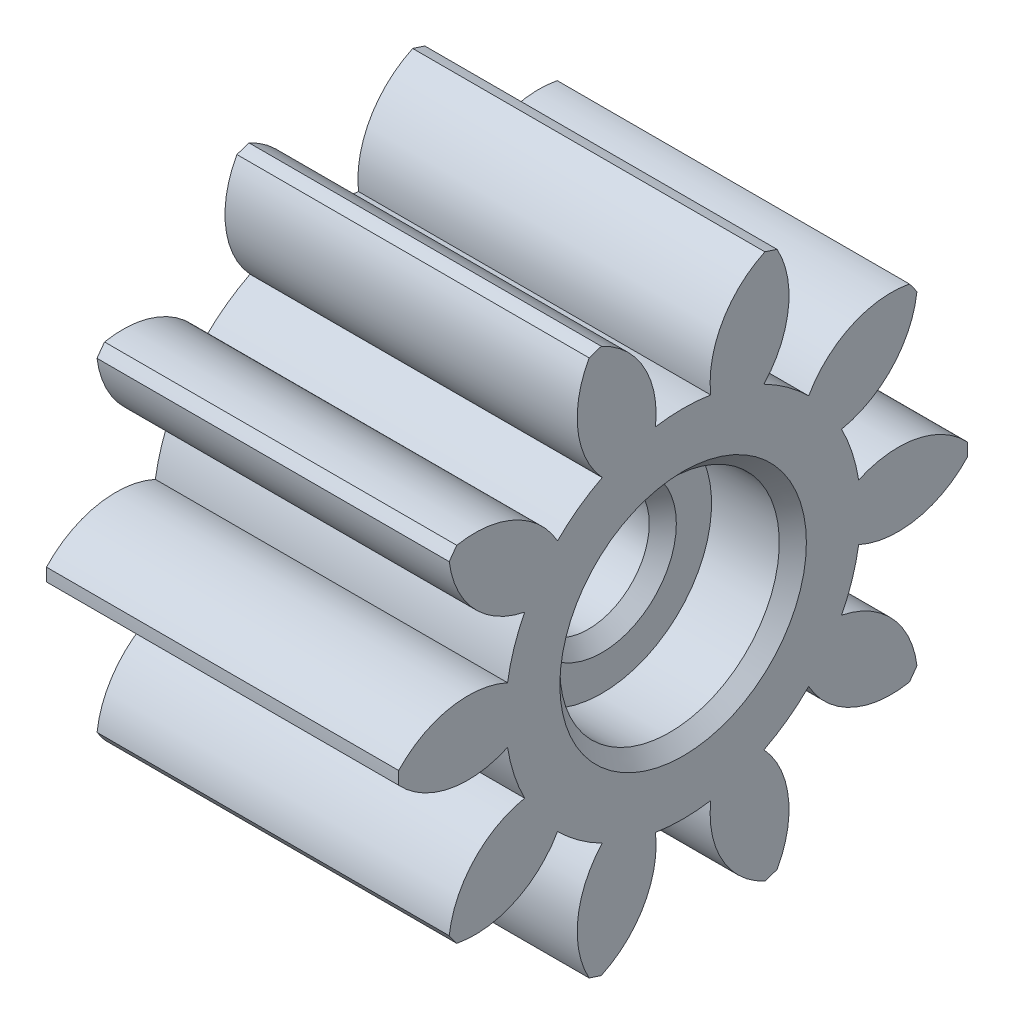
SolidWorks part; units mm, degrees
ref_plane "Plane1" through (0, 0, 0) normal (0, 0, 1) x (1, 0, 0)
ref_plane "Plane2" through (0, 0, 0) normal (0, 1, 0) x (1, 0, 0)
ref_plane "Plane3" through (0, 0, 0) normal (1, 0, 0) x (0, 0, -1)
sketch "HoldingSke" plane through (0, 0, 0) normal (0, 1, 0) x (1, 0, 0)
  line L0 (0, 0) -> (0.5627, -0.0992)
  line L1 (-15, 0) -> (100, 0) construction
  line L2 (0, 0) -> (-2.1039, 2.3779)
  line L3 (0, 0) -> (-11.863, 4.5341)
  line L4 (0, 0) -> (8.5048, 1.4996)
  line L5 (0, 0) -> (-46.8476, -17.4728)
  line L6 (0, 0) -> (-10.7765, -7.2709)
  line L7 (-2.1039, 2.3779) -> (8.6586, 51.2059)
  line L8 (-76.2, 54.61) -> (-75.7, 54.61)
  line L9 (-71.009, 38.7566) -> (-53.1078, 45.2721)
  line L10 (-76.2, 71.12) -> (104.1128, 71.12)
  line L11 (0, 0) -> (-13, 0)
  line L12 (-76.2, 101.6) -> (-76.147, 101.6)
  line L13 (24.9733, 27.94) -> (52.9518, 28.4284)
  line L14 (24.9733, 27.94) -> (24.9743, 27.94)
  line L15 (24.9733, 27.94) -> (100.4006, 29.5858)
  line L16 (-63.627, -1.75) -> (-12.827, -1.75)
  circle A0 centre (0, 0) radius 1.5
  circle A1 centre (0, 0) radius 6.5615
  circle A2 centre (0, 0) radius 37.5
  circle A3 centre (0, 0) radius 1.5
  dimension "MHD" = 13.123
  dimension "Hub_dia" = 75
  dimension "Bore" = 3
  dimension "MBD" = 3
  dimension "Num_teeth" = 10
  dimension "Pitch" = 0.5714
  dimension "Overall_len" = 50
  dimension "Show_teeth" = 10
  dimension "Thickness" = 13
  dimension "OAL" = 50.0001
  dimension "T_dim" = 0.5
  dimension "Ap" = 20
  dimension "H" = 19.05
  dimension "Pitch_radius" = 180.3128
  dimension "Width" = 13
  dimension "Backlash" = 0.053
  dimension "Addendum_fac" = 1
  dimension "Dedendum_fac" = 1.25
  dimension "Clearance_fac" = 0.25
  dimension "Dedendum_add" = 0.001
  dimension "Module" = 1.75
sketch "BasProSke" plane through (0, 0, 0) normal (0, 1, 0) x (1, 0, 0)
  line L0 (-10, 0) -> (60, 0) construction
  line L1 (0, 0) -> (0, 10.5)
  line L2 (0, 0) -> (13, 0)
  line L3 (13, 0) -> (13, 10.5)
  line L4 (13, 10.5) -> (0, 10.5)
  dimension "Thickness" = 13
  dimension "Diameter" = 21
revolve "Base-Revolve" add sketch "BasProSke" angle 360 about L0
sketch "TooCutSke" plane through (0, 0, 0) normal (1, 0, 0) x (0, 0, -1)
  line L1 (0, 0) -> (0, 107) construction
  line L2 (0, 0) -> (-1.4614, 8.6271) construction
  line L3 (0, 0) -> (-5.35, 16.4656) construction
  line L4 (-1.4614, 8.6271) -> (-2.675, 8.2328) construction
  arc A0 (1.0196, 6.4818) -> (-1.0196, 6.4818) centre (0, 0) ccw
  arc A1 (3.0536, 10.0727) -> (-3.0536, 10.0727) centre (0, 0) ccw
  circle A2 centre (0, 0) radius 8.75 construction
  circle A3 centre (0, 0) radius 8.2223 construction
  arc A4 (-1.0196, 6.4818) -> (-3.0536, 10.0727) centre (-4.4964, 6.8839) ccw
  arc A5 (3.0536, 10.0727) -> (1.0196, 6.4818) centre (4.4964, 6.8839) ccw
  dimension "Root_dia" = 13.123
  dimension "Overcut_dia" = 21.0508
  dimension "Pitch_dia" = 17.5
  dimension "Base_dia" = 16.4446
  dimension "Flank_rad" = 3.5
  dimension "Half_ang" = 18
  dimension "Half_CT" = 1.2761
extrude "ToothCut" cut sketch "TooCutSke" along normal through all
fillet "Breaks" [suppressed] radius 0.035
fillet "RootFillets" [suppressed] radius 0.4385
pattern_circular "TeethCuts" count 10 every 36 about axis through (-10, 0, 0) along (1, 0, 0) of "ToothCut", "RootFillets", "Breaks"
sketch "HubNeaOneSke" plane through (0, 0, 0) normal (-1, 0, 0) x (0, 0, 1)
  circle A0 centre (0, 0) radius 6.5615
  dimension "Diameter" = 13.123
extrude "HubNearOne" [suppressed] add sketch "HubNeaOneSke" along normal blind 37.0001
sketch "HubNeaBotSke" plane through (0, 0, 0) normal (-1, 0, 0) x (0, 0, 1)
  circle A0 centre (0, 0) radius 6.5615
  dimension "Diameter" = 13.123
extrude "HubNearBoth" [suppressed] add sketch "HubNeaBotSke" along normal blind 18.5
ref_plane "FarPln" through (13, 0, 0) normal (1, 0, 0) x (0, 0, -1)
sketch "HubFarSke" plane through (13, 0, 0) normal (1, 0, 0) x (0, 0, -1)
  circle A0 centre (0, 0) radius 6.5615
  dimension "Diameter" = 13.123
extrude "HubFar" [suppressed] add sketch "HubFarSke" along normal blind 18.5
sketch "BorSke" plane through (0, 0, 0) normal (1, 0, 0) x (0, 0, -1)
  circle A0 centre (0, 0) radius 1.5
  dimension "Diameter" = 3
extrude "Bore" cut sketch "BorSke" along normal mid plane 100.0001
sketch "KeySke" plane through (0, 0, 0) normal (1, 0, 0) x (0, 0, -1)
  line L0 (-0.6, 0) -> (-0.6, 2)
  line L1 (-0.6, 2) -> (0.6, 2)
  line L2 (0.6, 2) -> (0.6, 0)
  line L3 (0, 0) -> (0, 34) construction
  line L4 (-0.6, 0) -> (0.6, 0)
  dimension "Offset" = 2
  dimension "Width" = 1.2
extrude "Keyway" [suppressed] cut sketch "KeySke" along normal mid plane 100.0001
pattern_circular "Keyway2" [suppressed] count 2 every 90 about axis through (-10, 0, 0) along (1, 0, 0)
sketch "Sketch1" plane through (0, 0, 0) normal (-1, 0, 0) x (0, 0, 1)
  circle A0 centre (0, 0) radius 4.05
  dimension "D1" = 8.1
extrude "Cut-Extrude1" cut sketch "Sketch1" against normal blind 3
ref_plane "Plane4" through (6.5, 0, 0) normal (1, 0, 0) x (0, 0, -1)
mirror "Mirror1" about plane through (6.5, 0, 0) normal (1, 0, 0) of "Cut-Extrude1"
sketch "Sketch2" plane through (10, 0, 0) normal (1, 0, 0) x (0, 0, -1)
  circle A0 centre (0, 0) radius 2.25
  dimension "D1" = 4.5
extrude "Cut-Extrude2" cut sketch "Sketch2" against normal up to next
chamfer "Chamfer1" distance 0.5 angle 45 4 edges at (13, 0, 4.05) (10, 0, -2.25) (3, 0, 2.25) (0, 0, 4.05)
equation "' \"Module@HoldingSke\" = 6.35"
equation "' \"Num_teeth@HoldingSke\" = 12"
equation "' \"Ap@HoldingSke\" =  20"
equation "' \"Ap@HoldingSke\" = 20"
equation "' \"Width@HoldingSke\" = 0.5 * 25.4"
equation "' \"Hub_dia@HoldingSke\"= 1 * 25.4"
equation "' \"Hub_dia@HoldingSke\" = 1 * 25.4"
equation "' \"Overall_len@HoldingSke\" = 1.0 * 25.4"
equation "' \"Bore@HoldingSke\" = 0.75 * 25.4"
equation "' \"T_dim@HoldingSke\" = 0.1 * 25.4"
equation "' \"Width@KeySke\" = 0.25 * 25.4"
equation "' \"Show_teeth@HoldingSke\" = 13"
equation "' \"Backlash@HoldingSke\" = 0.009 * 25.4"
equation "' \"Addendum_fac@HoldingSke\" = 1.0"
equation "' \"Dedendum_fac@HoldingSke\" = 1.25"
equation "' \"Dedendum_add@HoldingSke\" = 0.00005 * 25.4"
equation "' \"Clearance_fac@HoldingSke\" = 0.25"
equation "\"Pitch@HoldingSke\" = 1 / \"Module@HoldingSke\""
equation "\"Overcut_dia@TooCutSke\" = (\"Num_teeth@HoldingSke\" + 2 * \"Addendum_fac@HoldingSke\") / \"Pitch@HoldingSke\" + 0.002 * 25.4"
equation "\"Pitch_dia@TooCutSke\" = \"Num_teeth@HoldingSke\" / \"Pitch@HoldingSke\""
equation "\"Base_dia@TooCutSke\" = \"Num_teeth@HoldingSke\" / \"Pitch@HoldingSke\" * cos((\"Ap@HoldingSke\"  * 3.14159265 / 180))"
equation "\"Root_dia@TooCutSke\" = (\"Num_teeth@HoldingSke\" + 2) / \"Pitch@HoldingSke\" - 2 * (\"Addendum_fac@HoldingSke\" + \"Dedendum_fac@HoldingSke\") / \"Pitch@HoldingSke\" - \"Dedendum_add@HoldingSke\" * 2"
equation "\"Half_ang@TooCutSke\" = 180 / \"Num_teeth@HoldingSke\""
equation "\"Half_CT@TooCutSke\" = \"Num_teeth@HoldingSke\" / \"Pitch@HoldingSke\" * sin((3.14159265 / 2 / \"Num_teeth@HoldingSke\")) / 2 - 7 * \"Backlash@HoldingSke\" / 4"
equation "\"Flank_rad@TooCutSke\" = \"Num_teeth@HoldingSke\" / \"Pitch@HoldingSke\" / 5"
equation "\"Radius@RootFillets\" = \"Clearance_fac@HoldingSke\" / \"Pitch@HoldingSke\" + \"Dedendum_add@HoldingSke\""
equation "\"Break_rad@Breaks\" = 0.02 / \"Pitch@HoldingSke\""
equation "\"Thickness@HoldingSke\" = \"Width@HoldingSke\""
equation "\"OAL@HoldingSke\" = \"Thickness@HoldingSke\""
equation "\"MHD@HoldingSke\" = (\"Num_teeth@HoldingSke\" + 2) / \"Pitch@HoldingSke\" - 2 * (\"Addendum_fac@HoldingSke\" + \"Dedendum_fac@HoldingSke\")  / \"Pitch@HoldingSke\" - \"Dedendum_add@HoldingSke\" * 2"
equation "\"MBD@HoldingSke\" = (\"Num_teeth@HoldingSke\" + 2) / \"Pitch@HoldingSke\" - 2 * (\"Addendum_fac@HoldingSke\" + \"Dedendum_fac@HoldingSke\")  / \"Pitch@HoldingSke\" - \"Dedendum_add@HoldingSke\" * 2 - 0.002 * 25.4"
equation "\"MHD@HoldingSke\" = ((sgn( \"MHD@HoldingSke\" - \"Hub_dia@HoldingSke\" )-1)*( \"MHD@HoldingSke\" - \"Hub_dia@HoldingSke\" ))/-2+ \"Hub_dia@HoldingSke\""
equation "\"MBD@HoldingSke\" = ((sgn( \"MBD@HoldingSke\" - \"Bore@HoldingSke\" )-1)*( \"MBD@HoldingSke\" - \"Bore@HoldingSke\" ))/-2+ \"Bore@HoldingSke\""
equation "\"OAL@HoldingSke\" = ((sgn( \"OAL@HoldingSke\" - \"Overall_len@HoldingSke\" )+1)*( \"OAL@HoldingSke\" - \"Overall_len@HoldingSke\" ))/2 + \"Overall_len@HoldingSke\" + 0.000002 * 25.4"
equation "\"Num_teeth@TeethCuts\" = int( \"Show_teeth@HoldingSke\" ) + 1"
equation "\"Num_teeth@TeethCuts\" = ((sgn( \"Num_teeth@TeethCuts\" - \"Num_teeth@HoldingSke\" )-1)*( \"Num_teeth@TeethCuts\" - \"Num_teeth@HoldingSke\" ))/-2+ \"Num_teeth@HoldingSke\""
equation "\"Num_teeth@TeethCuts\" = ((sgn( \"Num_teeth@TeethCuts\" - 2.0)+1)*( \"Num_teeth@TeethCuts\" - 2.0))/2 +2.0"
equation "\"Angle@TeethCuts\" = 360.0 / \"Num_teeth@HoldingSke\""
equation "\"Diameter@BasProSke\" = (\"Num_teeth@HoldingSke\" + 2 * \"Addendum_fac@HoldingSke\") / \"Pitch@HoldingSke\""
equation "\"Thickness@BasProSke\"  = \"Thickness@HoldingSke\""
equation "' \"Fillet_rad@BasProSke\" =  \"Thickness@HoldingSke\" * 0.05"
equation "' \"Fillet_rad@BasProSke\" = \"Thickness@HoldingSke\" * 0.05"
equation "\"MHD@HoldingSke\" = ((sgn( \"MHD@HoldingSke\" - \"Root_dia@TooCutSke\" )-1)*( \"MHD@HoldingSke\" - \"Root_dia@TooCutSke\" ))/-2+ \"Root_dia@TooCutSke\""
equation "\"Diameter@HubNeaOneSke\" = \"MHD@HoldingSke\""
equation "\"Length@HubNearOne\" = \"OAL@HoldingSke\" - \"Thickness@BasProSke\""
equation "\"Diameter@HubNeaBotSke\" = \"MHD@HoldingSke\""
equation "\"Length@HubNearBoth\" = ( \"OAL@HoldingSke\" - \"Thickness@BasProSke\" ) / 2.0"
equation "\"Thickness@FarPln\" = \"Thickness@BasProSke\""
equation "\"Diameter@HubFarSke\" = \"MHD@HoldingSke\""
equation "\"Length@HubFar\" = ( \"OAL@HoldingSke\" - \"Thickness@BasProSke\" ) / 2.0"
equation "\"Diameter@BorSke\" = \"MBD@HoldingSke\""
equation "\"D1@Bore\" = \"OAL@HoldingSke\" * 2.0"
equation "\"D1@Keyway\" = \"OAL@HoldingSke\" * 2.0"
equation "\"Offset@KeySke\" = \"T_dim@HoldingSke\" + \"MBD@HoldingSke\" / 2.0"
